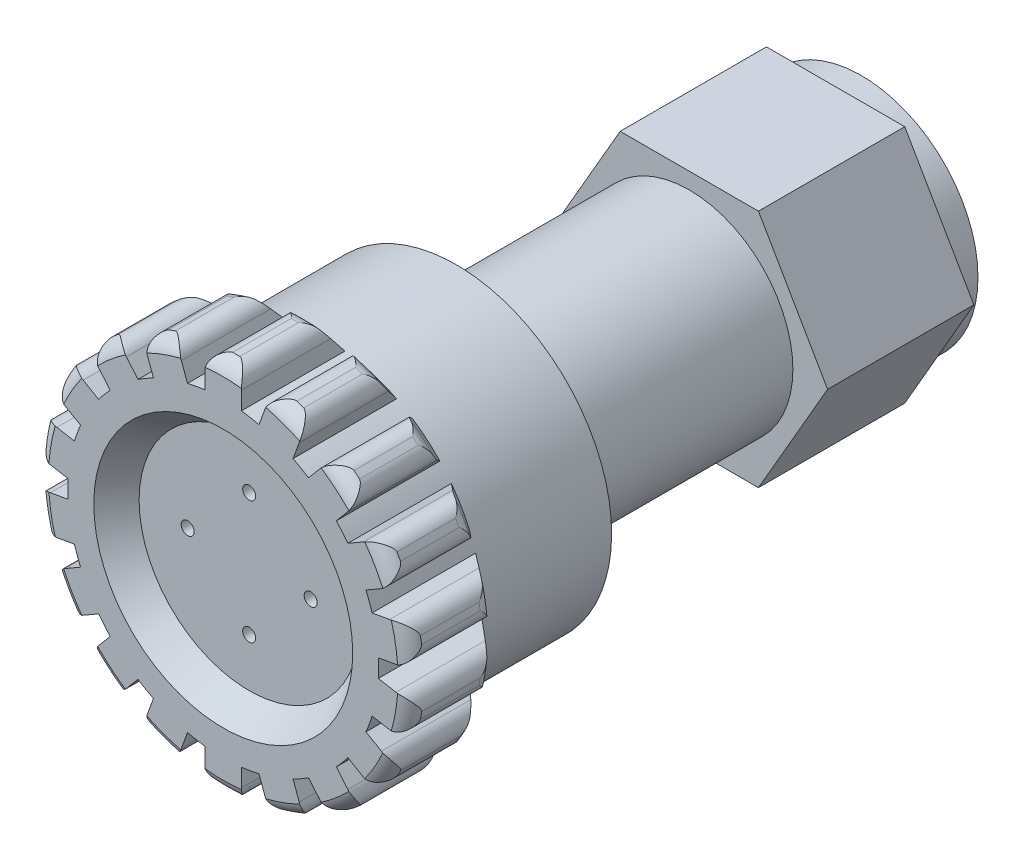
SolidWorks part; units mm, degrees
ref_plane "前视基准面" through (0, 0, 0) normal (0, 0, 1) x (1, 0, 0)
ref_plane "上视基准面" through (0, 0, 0) normal (0, 1, 0) x (1, 0, 0)
ref_plane "右视基准面" through (0, 0, 0) normal (1, 0, 0) x (0, 0, -1)
sketch "草图1" plane through (0, 0, 0) normal (0, 0, 1) x (1, 0, 0)
  circle A0 centre (0, 0) radius 9
  circle A1 centre (0, 0) radius 6
  dimension "D1" = 18
  dimension "D2" = 12
extrude "凸台-拉伸1" add sketch "草图1" along normal blind 2
sketch "草图2" plane through (0, 0, 2) normal (0, 0, 1) x (1, 0, 0)
  line L1 (10.681, 0) -> (5.3405, 9.25)
  line L2 (5.3405, 9.25) -> (-5.3405, 9.25)
  line L3 (-5.3405, 9.25) -> (-10.681, 0)
  line L4 (-10.681, 0) -> (-5.3405, -9.25)
  line L5 (-5.3405, -9.25) -> (5.3405, -9.25)
  line L6 (5.3405, -9.25) -> (10.681, 0)
  circle A0 centre (0, 0) radius 6 construction
  circle A1 centre (0, 0) radius 6
  circle A2 centre (0, 0) radius 9.25 construction
  dimension "D1" = 18.5
extrude "凸台-拉伸2" add sketch "草图2" along normal blind 11.3
sketch "草图3" plane through (0, 0, 13.3) normal (0, 0, 1) x (1, 0, 0)
  circle A0 centre (0, 0) radius 6 construction
  circle A1 centre (0, 0) radius 6
  circle A2 centre (0, 0) radius 8
  point P0 (0.1244, 0)
  point P5 (0, 0)
  dimension "D1" = 16
extrude "凸台-拉伸3" add sketch "草图3" along normal blind 18
sketch "草图4" plane through (0, 0, 31.3) normal (0, 0, 1) x (1, 0, 0)
  circle A0 centre (0, 0) radius 12
  dimension "D1" = 24
extrude "凸台-拉伸4" add sketch "草图4" along normal blind 18
sketch "草图6" plane through (0, 0, 49.3) normal (0, 0, 1) x (1, 0, 0)
  line L0 (2.7606, 11.6781) -> (3.2333, 12.9767)
  line L1 (-1.4, 11.9181) -> (1.4, 11.9181)
  line L2 (-1.4, 11.9181) -> (-1.4, 13.3)
  line L3 (-0.2, 14.5) -> (0.2, 14.5)
  line L4 (1.4, 11.9181) -> (1.4, 13.3)
  line L5 (2.7606, 11.6781) -> (5.3918, 10.7205)
  line L6 (5.3918, 10.7205) -> (5.8644, 12.0191)
  line L7 (4.7714, 13.6939) -> (5.1472, 13.5571)
  line L8 (6.5883, 10.0297) -> (7.4766, 11.0883)
  line L9 (6.5883, 10.0297) -> (8.7332, 8.2299)
  line L10 (8.7332, 8.2299) -> (9.6215, 9.2885)
  line L11 (9.1672, 11.2362) -> (9.4736, 10.9791)
  line L12 (9.6213, 7.1715) -> (10.8181, 7.8624)
  line L13 (9.6213, 7.1715) -> (11.0213, 4.7466)
  line L14 (11.0213, 4.7466) -> (12.2181, 5.4376)
  line L15 (12.4574, 7.4232) -> (12.6574, 7.0768)
  line L16 (11.4939, 3.4483) -> (12.8548, 3.6883)
  line L17 (11.4939, 3.4483) -> (11.9801, 0.6908)
  line L18 (11.9801, 0.6908) -> (13.3411, 0.9308)
  line L19 (14.245, 2.7149) -> (14.3144, 2.3209)
  line L20 (11.9801, -0.6908) -> (13.3411, -0.9308)
  line L21 (11.9801, -0.6908) -> (11.4939, -3.4483)
  line L22 (11.4939, -3.4483) -> (12.8548, -3.6883)
  line L23 (14.3144, -2.3209) -> (14.245, -2.7149)
  line L24 (11.0213, -4.7466) -> (12.2181, -5.4376)
  line L25 (11.0213, -4.7466) -> (9.6213, -7.1715)
  line L26 (9.6213, -7.1715) -> (10.8181, -7.8624)
  line L27 (12.6574, -7.0768) -> (12.4574, -7.4232)
  line L28 (8.7332, -8.2299) -> (9.6215, -9.2885)
  line L29 (8.7332, -8.2299) -> (6.5883, -10.0297)
  line L30 (6.5883, -10.0297) -> (7.4766, -11.0883)
  line L31 (9.4736, -10.9791) -> (9.1672, -11.2362)
  line L32 (5.3918, -10.7205) -> (5.8644, -12.0191)
  line L33 (5.3918, -10.7205) -> (2.7606, -11.6781)
  line L34 (2.7606, -11.6781) -> (3.2333, -12.9767)
  line L35 (5.1472, -13.5571) -> (4.7714, -13.6939)
  line L36 (1.4, -11.9181) -> (1.4, -13.3)
  line L37 (1.4, -11.9181) -> (-1.4, -11.9181)
  line L38 (-1.4, -11.9181) -> (-1.4, -13.3)
  line L39 (0.2, -14.5) -> (-0.2, -14.5)
  line L40 (-2.7606, -11.6781) -> (-3.2333, -12.9767)
  line L41 (-2.7606, -11.6781) -> (-5.3918, -10.7205)
  line L42 (-5.3918, -10.7205) -> (-5.8644, -12.0191)
  line L43 (-4.7714, -13.6939) -> (-5.1472, -13.5571)
  line L44 (-6.5883, -10.0297) -> (-7.4766, -11.0883)
  line L45 (-6.5883, -10.0297) -> (-8.7332, -8.2299)
  line L46 (-8.7332, -8.2299) -> (-9.6215, -9.2885)
  line L47 (-9.1672, -11.2362) -> (-9.4736, -10.9791)
  line L48 (-9.6213, -7.1715) -> (-10.8181, -7.8624)
  line L49 (-9.6213, -7.1715) -> (-11.0213, -4.7466)
  line L50 (-11.0213, -4.7466) -> (-12.2181, -5.4376)
  line L51 (-12.4574, -7.4232) -> (-12.6574, -7.0768)
  line L52 (-11.4939, -3.4483) -> (-12.8548, -3.6883)
  line L53 (-11.4939, -3.4483) -> (-11.9801, -0.6908)
  line L54 (-11.9801, -0.6908) -> (-13.3411, -0.9308)
  line L55 (-14.245, -2.7149) -> (-14.3144, -2.3209)
  line L56 (-11.9801, 0.6908) -> (-13.3411, 0.9308)
  line L57 (-11.9801, 0.6908) -> (-11.4939, 3.4483)
  line L58 (-11.4939, 3.4483) -> (-12.8548, 3.6883)
  line L59 (-14.3144, 2.3209) -> (-14.245, 2.7149)
  line L60 (-11.0213, 4.7466) -> (-12.2181, 5.4376)
  line L61 (-11.0213, 4.7466) -> (-9.6213, 7.1715)
  line L62 (-9.6213, 7.1715) -> (-10.8181, 7.8624)
  line L63 (-12.6574, 7.0768) -> (-12.4574, 7.4232)
  line L64 (-8.7332, 8.2299) -> (-9.6215, 9.2885)
  line L65 (-8.7332, 8.2299) -> (-6.5883, 10.0297)
  line L66 (-6.5883, 10.0297) -> (-7.4766, 11.0883)
  line L67 (-9.4736, 10.9791) -> (-9.1672, 11.2362)
  line L68 (-5.3918, 10.7205) -> (-5.8644, 12.0191)
  line L69 (-5.3918, 10.7205) -> (-2.7606, 11.6781)
  line L70 (-2.7606, 11.6781) -> (-3.2333, 12.9767)
  line L71 (-5.1472, 13.5571) -> (-4.7714, 13.6939)
  circle A0 centre (0, 0) radius 12 construction
  arc A1 (0.2, 14.5) -> (1.4, 13.3) centre (0.2, 13.3) cw
  arc A2 (-1.4, 13.3) -> (-0.2, 14.5) centre (-0.2, 13.3) cw
  arc A3 (3.2333, 12.9767) -> (4.7714, 13.6939) centre (4.3609, 12.5663) cw
  arc A4 (5.1472, 13.5571) -> (5.8644, 12.0191) centre (4.7368, 12.4295) cw
  arc A5 (7.4766, 11.0883) -> (9.1672, 11.2362) centre (8.3959, 10.3169) cw
  arc A6 (9.4736, 10.9791) -> (9.6215, 9.2885) centre (8.7023, 10.0598) cw
  arc A7 (10.8181, 7.8624) -> (12.4574, 7.4232) centre (11.4181, 6.8232) cw
  arc A8 (12.6574, 7.0768) -> (12.2181, 5.4376) centre (11.6181, 6.4768) cw
  arc A9 (12.8548, 3.6883) -> (14.245, 2.7149) centre (13.0632, 2.5065) cw
  arc A10 (14.3144, 2.3209) -> (13.3411, 0.9308) centre (13.1327, 2.1126) cw
  arc A11 (13.3411, -0.9308) -> (14.3144, -2.3209) centre (13.1327, -2.1126) cw
  arc A12 (14.245, -2.7149) -> (12.8548, -3.6883) centre (13.0632, -2.5065) cw
  arc A13 (12.2181, -5.4376) -> (12.6574, -7.0768) centre (11.6181, -6.4768) cw
  arc A14 (12.4574, -7.4232) -> (10.8181, -7.8624) centre (11.4181, -6.8232) cw
  arc A15 (9.6215, -9.2885) -> (9.4736, -10.9791) centre (8.7023, -10.0598) cw
  arc A16 (9.1672, -11.2362) -> (7.4766, -11.0883) centre (8.3959, -10.3169) cw
  arc A17 (5.8644, -12.0191) -> (5.1472, -13.5571) centre (4.7368, -12.4295) cw
  arc A18 (4.7714, -13.6939) -> (3.2333, -12.9767) centre (4.3609, -12.5663) cw
  arc A19 (1.4, -13.3) -> (0.2, -14.5) centre (0.2, -13.3) cw
  arc A20 (-0.2, -14.5) -> (-1.4, -13.3) centre (-0.2, -13.3) cw
  arc A21 (-3.2333, -12.9767) -> (-4.7714, -13.6939) centre (-4.3609, -12.5663) cw
  arc A22 (-5.1472, -13.5571) -> (-5.8644, -12.0191) centre (-4.7368, -12.4295) cw
  arc A23 (-7.4766, -11.0883) -> (-9.1672, -11.2362) centre (-8.3959, -10.3169) cw
  arc A24 (-9.4736, -10.9791) -> (-9.6215, -9.2885) centre (-8.7023, -10.0598) cw
  arc A25 (-10.8181, -7.8624) -> (-12.4574, -7.4232) centre (-11.4181, -6.8232) cw
  arc A26 (-12.6574, -7.0768) -> (-12.2181, -5.4376) centre (-11.6181, -6.4768) cw
  arc A27 (-12.8548, -3.6883) -> (-14.245, -2.7149) centre (-13.0632, -2.5065) cw
  arc A28 (-14.3144, -2.3209) -> (-13.3411, -0.9308) centre (-13.1327, -2.1126) cw
  arc A29 (-13.3411, 0.9308) -> (-14.3144, 2.3209) centre (-13.1327, 2.1126) cw
  arc A30 (-14.245, 2.7149) -> (-12.8548, 3.6883) centre (-13.0632, 2.5065) cw
  arc A31 (-12.2181, 5.4376) -> (-12.6574, 7.0768) centre (-11.6181, 6.4768) cw
  arc A32 (-12.4574, 7.4232) -> (-10.8181, 7.8624) centre (-11.4181, 6.8232) cw
  arc A33 (-9.6215, 9.2885) -> (-9.4736, 10.9791) centre (-8.7023, 10.0598) cw
  arc A34 (-9.1672, 11.2362) -> (-7.4766, 11.0883) centre (-8.3959, 10.3169) cw
  arc A35 (-5.8644, 12.0191) -> (-5.1472, 13.5571) centre (-4.7368, 12.4295) cw
  arc A36 (-4.7714, 13.6939) -> (-3.2333, 12.9767) centre (-4.3609, 12.5663) cw
  point P150 (0, 0)
  dimension "D4" = 1.2
  dimension "D1" = 1.4
  dimension "D2" = 1.4
  dimension "D3" = 14.5
  dimension "D5" = 18
extrude "凸台-拉伸5" add sketch "草图6" against normal blind 8
sketch "草图8" plane through (0, 0, 0) normal (1, 0, 0) x (0, 0, -1)
  line L0 (-41.3, 12) -> (-41.3, 14.5)
  line L1 (-41.3, 12.0191) -> (-41.3, 10.7205) construction
  line L4 (-41.3, 14.5) -> (-49.3, 14.5) construction
  line L5 (-42.9998, 14.1247) -> (-41.3, 12)
  line L7 (0, 0) -> (-49.3, 0) construction
  line L8 (-49.3, 0.6908) -> (-49.3, -0.6908) construction
  line L9 (-47.3, 0) -> (-47.3, 8.5)
  line L10 (-47.3, 8.5) -> (-49.3, 10)
  line L11 (-49.3, 9.2885) -> (-49.3, 8.2299) construction
  line L12 (-49.3, 10) -> (-49.3, 0)
  line L13 (-49.3, 0) -> (-47.3, 0)
  line L17 (-41.3, 14.7652) -> (-41.3, 14.5)
  line L18 (-49.3, 13.5) -> (-49.3, 14.5)
  line L19 (-49.3, 13.5571) -> (-49.3, 12.0191) construction
  line L21 (-41.3, 14.5) -> (-49.3, 14.5) construction
  line L22 (-48.3, 14.5) -> (-43.7806, 14.5)
  line L23 (-49.3, 14.5) -> (-49.3, 14.7652)
  line L24 (-49.3, 14.7652) -> (-41.3, 14.7652)
  arc A0 (-43.7806, 14.5) -> (-42.9998, 14.1247) centre (-43.7806, 13.5) cw
  arc A1 (-49.3, 13.5) -> (-48.3, 14.5) centre (-47.8805, 13.0805) cw
  point P7 (-43.3, 14.5)
  dimension "D2" = 1
  dimension "D1" = 2
  dimension "D3" = 8.5
  dimension "D4" = 10
  dimension "D5" = 2
  dimension "D6" = 1
  dimension "D7" = 1
revolve "切除-旋转4" cut sketch "草图8" angle 360 about L7
sketch "草图9" plane through (0, 0, 47.3) normal (0, 0, 1) x (1, 0, 0)
  circle A0 centre (0, 4.75) radius 0.5
  circle A1 centre (4.75, 0) radius 0.5
  circle A2 centre (0, -4.75) radius 0.5
  circle A3 centre (-4.75, 0) radius 0.5
  point P8 (0, 0)
  point P10 (0, 0)
  dimension "D5" = 1
  dimension "D1" = 4.75
  dimension "D2" = 4.75
  dimension "D3" = 4.75
  dimension "D4" = 4.75
extrude "切除-拉伸1" cut sketch "草图9" against normal blind 18
